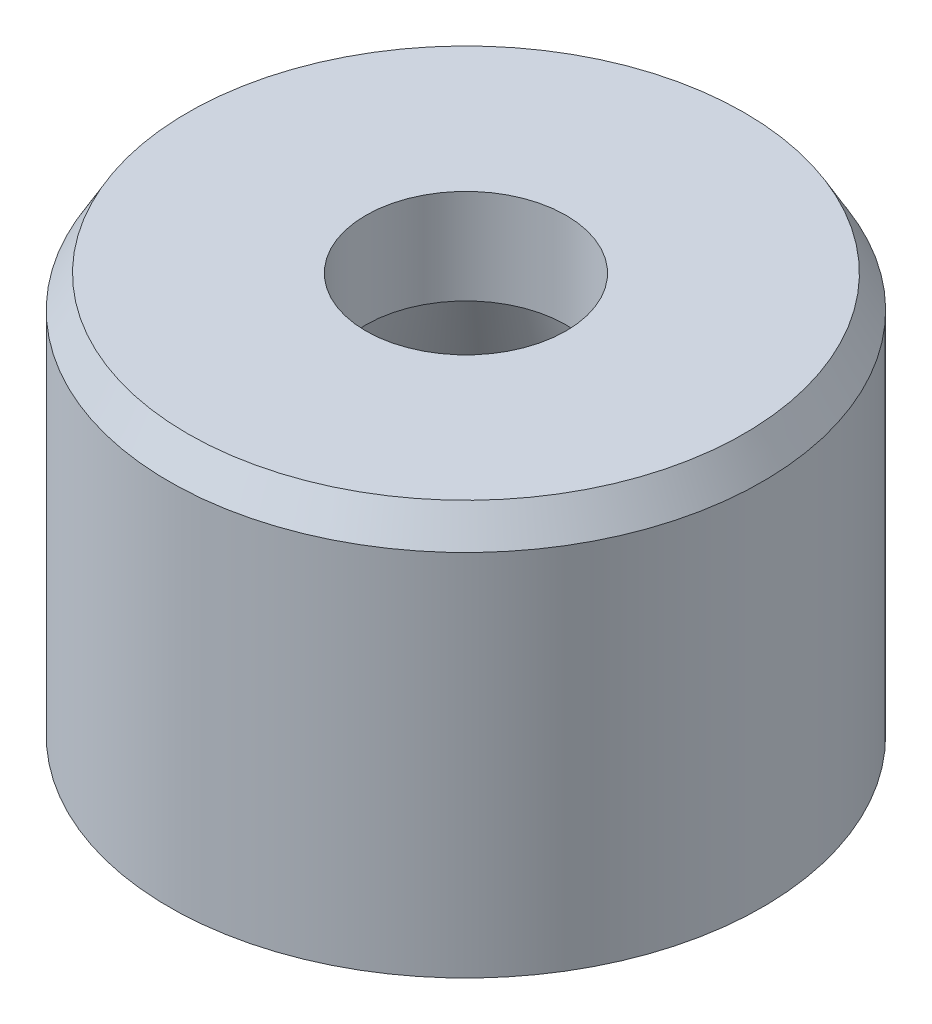
SolidWorks part; units mm, degrees
ref_plane "Front" through (0, 0, 0) normal (0, 0, 1) x (1, 0, 0)
ref_plane "Top" through (0, 0, 0) normal (0, 1, 0) x (1, 0, 0)
ref_plane "Right" through (0, 0, 0) normal (1, 0, 0) x (0, 0, -1)
sketch "Sketch1" plane through (0, 0, 0) normal (0, 1, 0) x (1, 0, 0)
  circle A0 centre (0, 0) radius 2.7
  circle A1 centre (0, 0) radius 8
  dimension "D1" = 5.4
  dimension "D2" = 16
extrude "Boss-Extrude1" add sketch "Sketch1" along normal blind 10.8
chamfer "Chamfer1" distance 3 angle 70 1 edges at (0, 0, 2.7)
chamfer "Chamfer2" distance 0.5 angle 60 1 edges at (0, 10.8, 8)
